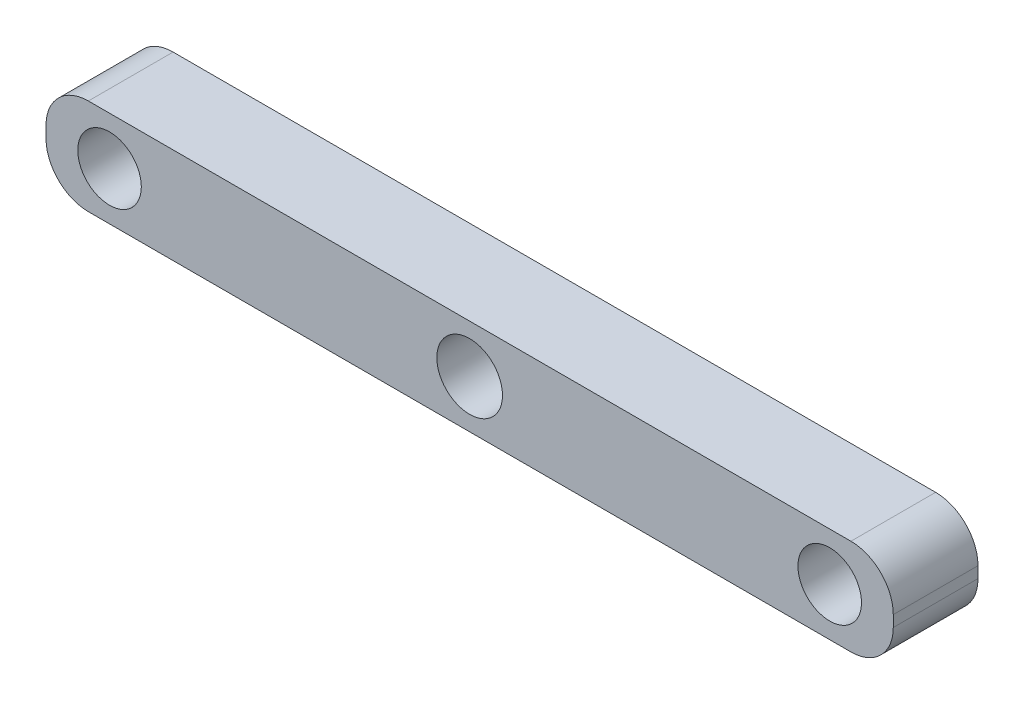
SolidWorks part; units mm, degrees
ref_plane "Front Plane" through (0, 0, 0) normal (0, 0, 1) x (1, 0, 0)
ref_plane "Top Plane" through (0, 0, 0) normal (0, 1, 0) x (1, 0, 0)
ref_plane "Right Plane" through (0, 0, 0) normal (1, 0, 0) x (0, 0, -1)
sketch "Sketch1" plane through (0, 0, 0) normal (0, 0, 1) x (1, 0, 0)
  line L0 (0, 2.2636) -> (0, -2.2636) construction
  line L1 (-18, -2.2636) -> (18, -2.2636)
  line L2 (-20, -0.2636) -> (-20, 0.2636)
  line L3 (-18, 2.2636) -> (18, 2.2636)
  line L4 (20, -0.2636) -> (20, 0.2636)
  line L5 (-20, -2.2636) -> (20, 2.2636) construction
  line L6 (-20, 2.2636) -> (20, -2.2636) construction
  circle A0 centre (0, 0) radius 1.55
  circle A1 centre (-17, 0) radius 1.5
  arc A2 (18, -2.2636) -> (20, -0.2636) centre (18, -0.2636) ccw
  arc A3 (18, 2.2636) -> (20, 0.2636) centre (18, 0.2636) cw
  arc A4 (-18, -2.2636) -> (-20, -0.2636) centre (-18, -0.2636) cw
  arc A5 (-20, 0.2636) -> (-18, 2.2636) centre (-18, 0.2636) cw
  circle A6 centre (17, 0) radius 1.5
  dimension "D1" = 3.1
  dimension "D3" = 3
  dimension "D4" = 2
  dimension "D2" = 40
  dimension "D5" = 17
extrude "Boss-Extrude1" add sketch "Sketch1" along normal blind 4
